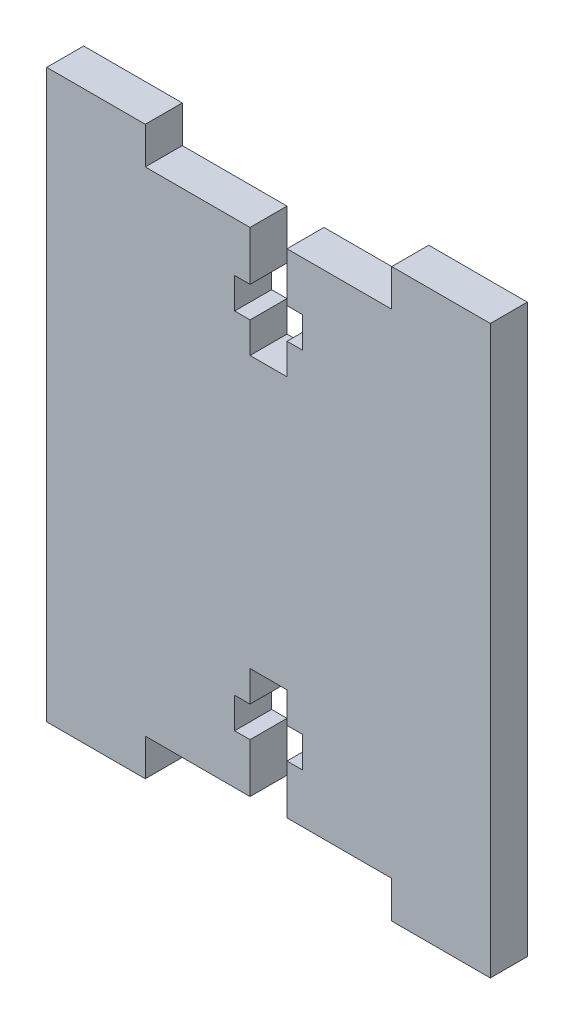
SolidWorks part; units mm, degrees
material "Pinho"
ref_plane "Plano frontal" through (0, 0, 0) normal (0, 0, 1) x (1, 0, 0)
ref_plane "Plano superior" through (0, 0, 0) normal (0, 1, 0) x (1, 0, 0)
ref_plane "Plano direito" through (0, 0, 0) normal (1, 0, 0) x (0, 0, -1)
sketch "Esboço1" plane through (0, 0, 0) normal (0, 0, 1) x (1, 0, 0)
  line L0 (2.25, 0) -> (-6.25, 0)
  line L1 (-6.25, 0) -> (-6.25, 2)
  line L2 (5.25, 0) -> (13.75, 0)
  line L3 (13.75, 0) -> (13.75, 2)
  line L4 (13.75, -42) -> (13.75, -43)
  line L6 (21.75, 2) -> (21.75, -42)
  line L7 (2.25, -4) -> (2.25, 0)
  line L8 (1, -4) -> (2.25, -4)
  line L9 (-14.25, 2) -> (-14.25, -42)
  line L11 (21.75, -42) -> (21.75, -43)
  line L12 (-14.25, -42) -> (-14.25, -43)
  line L14 (-6.25, -42) -> (-6.25, -43)
  line L15 (1, -36) -> (1, -33.5)
  line L16 (1, -33.5) -> (2.25, -33.5)
  line L17 (2.25, -31) -> (5.25, -31)
  line L18 (5.25, -4) -> (5.25, 0)
  line L19 (6.5, -4) -> (5.25, -4)
  line L20 (6.5, -6.5) -> (6.5, -4)
  line L21 (5.25, -6.5) -> (6.5, -6.5)
  line L22 (5.25, -9) -> (5.25, -6.5)
  line L23 (2.25, -6.5) -> (2.25, -9)
  line L24 (2.25, -9) -> (5.25, -9)
  line L25 (1, -6.5) -> (2.25, -6.5)
  line L26 (1, -4) -> (1, -6.5)
  line L27 (2.25, -33.5) -> (2.25, -31)
  line L28 (5.25, -31) -> (5.25, -33.5)
  line L29 (5.25, -33.5) -> (6.5, -33.5)
  line L30 (6.5, -33.5) -> (6.5, -36)
  line L31 (6.5, -36) -> (5.25, -36)
  line L32 (5.25, -36) -> (5.25, -40)
  line L33 (1, -36) -> (2.25, -36)
  line L34 (2.25, -36) -> (2.25, -40)
  line L35 (13.75, -40) -> (13.75, -42)
  line L36 (5.25, -40) -> (13.75, -40)
  line L37 (-6.25, -40) -> (-6.25, -42)
  line L38 (2.25, -40) -> (-6.25, -40)
  line L39 (-6.25, 2) -> (-6.25, 3)
  line L40 (-14.25, -43) -> (-6.25, -43)
  line L41 (-14.25, 3) -> (-6.25, 3)
  line L42 (-14.25, 2) -> (-14.25, 3)
  line L43 (13.75, -43) -> (21.75, -43)
  line L45 (21.75, 2) -> (21.75, 3)
  line L46 (21.75, 3) -> (13.75, 3)
  line L47 (13.75, 2) -> (13.75, 3)
  point P0 (9.5, -40)
  point P37 (-14.25, -20)
  point P39 (21.75, -20)
  dimension "D1" = 40
  dimension "D2" = 36
  dimension "D3" = 3
  dimension "D4" = 3
extrude "Ressalto-extrusão1" add sketch "Esboço1" along normal blind 3
